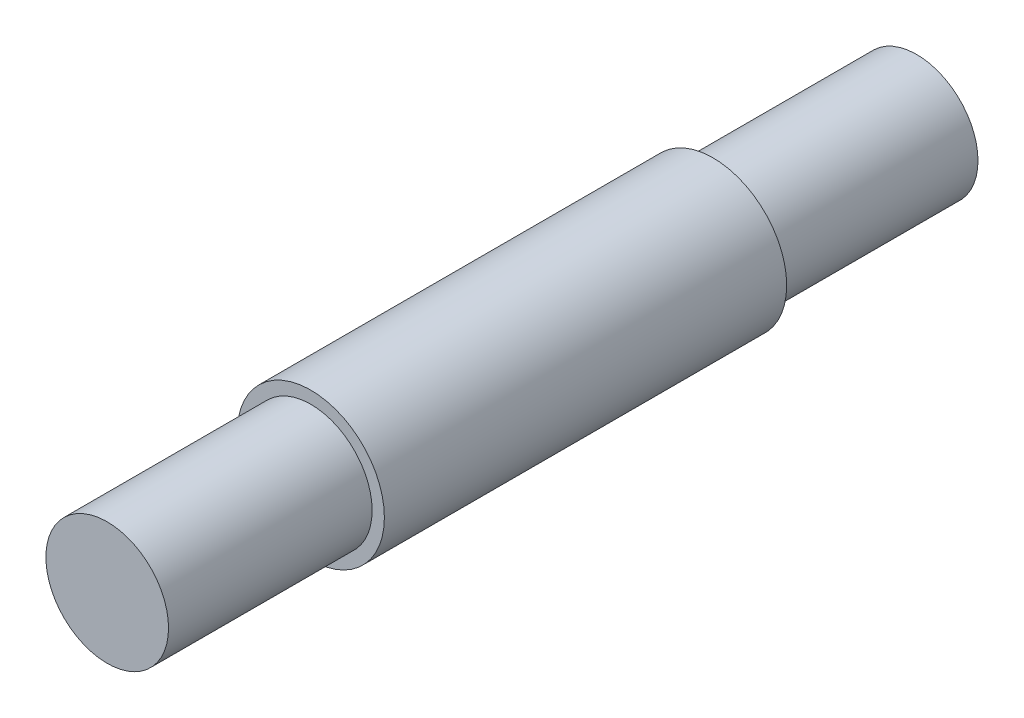
SolidWorks part; units mm, degrees
ref_plane "Front Plane" through (0, 0, 0) normal (0, 0, 1) x (1, 0, 0)
ref_plane "Top Plane" through (0, 0, 0) normal (0, 1, 0) x (1, 0, 0)
ref_plane "Right Plane" through (0, 0, 0) normal (1, 0, 0) x (0, 0, -1)
sketch "Sketch2" plane through (0, 0, 0) normal (0, 0, 1) x (1, 0, 0)
  circle A0 centre (0, 0) radius 25
extrude "Boss-Extrude1" add sketch "Sketch2" along normal blind 83
cosmetic thread "Cosmetic Thread2" parameters "D1"=70, "D2"=42.516
sketch "Sketch3" plane through (0, 0, 83) normal (0, 0, 1) x (1, 0, 0)
  circle A0 centre (0, 0) radius 30
extrude "Boss-Extrude2" add sketch "Sketch3" along normal blind 164
sketch "Sketch4" plane through (0, 0, 247) normal (0, 0, 1) x (1, 0, 0)
  circle A0 centre (0, 0) radius 25
extrude "Boss-Extrude3" add sketch "Sketch4" along normal blind 83
cosmetic thread "Cosmetic Thread1" parameters "D1"=70, "D2"=42.516
